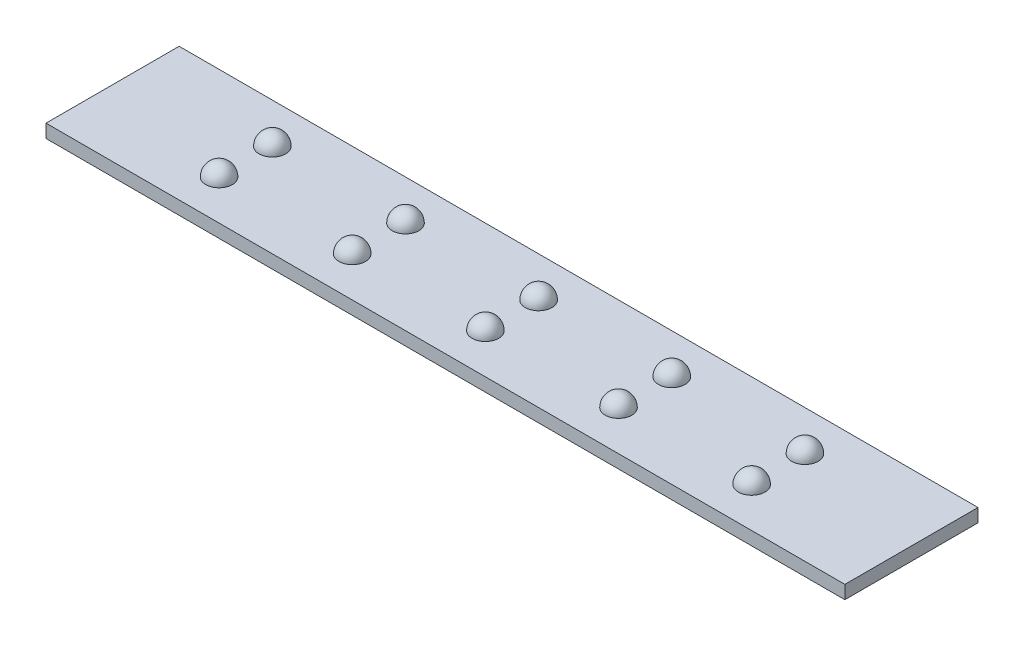
SolidWorks part; units mm, degrees
ref_plane "Front Plane" through (0, 0, 0) normal (0, 0, 1) x (1, 0, 0)
ref_plane "Top Plane" through (0, 0, 0) normal (0, 1, 0) x (1, 0, 0)
ref_plane "Right Plane" through (0, 0, 0) normal (1, 0, 0) x (0, 0, -1)
sketch "Sketch1" plane through (0, 0, 0) normal (0, 1, 0) x (1, 0, 0)
  line L0 (30, -5) -> (-30, -5)
  line L1 (30, -5) -> (30, 5)
  line L2 (-30, -5) -> (-30, 5)
  line L3 (30, 5) -> (-30, 5)
  line L4 (30, -5) -> (-30, 5) construction
  line L5 (-30, -5) -> (30, 5) construction
  point P1 (0, 0)
extrude "Boss-Extrude1" add sketch "Sketch1" along normal blind 1
sketch "Sketch3" plane through (0, 1, 0) normal (0, 1, 0) x (1, 0, 0)
  line L4 (-1, -2) -> (1, -2)
  arc A1 (-1, -2) -> (1, -2) centre (0, -2) ccw
revolve "Revolve1" add sketch "Sketch3" angle 180 about L4
pattern_linear "LPattern1" count 3 spacing 10 along (-1, 0, 0) count 2 spacing 4 along (0, 0, -1) of "Revolve1"
pattern_linear "LPattern2" count 3 spacing 10 along (1, 0, 0) of "LPattern1", "Revolve1"
